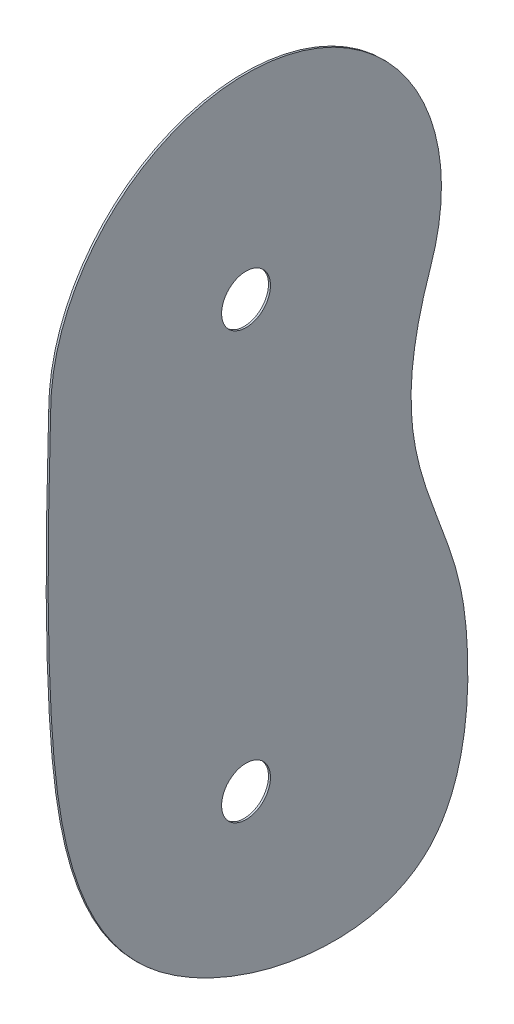
SolidWorks part; units mm, degrees
material "Teras S325"
ref_plane "Front Plane" through (0, 0, 0) normal (0, 0, 1) x (1, 0, 0)
ref_plane "Top Plane" through (0, 0, 0) normal (0, 1, 0) x (1, 0, 0)
ref_plane "Right Plane" through (0, 0, 0) normal (1, 0, 0) x (0, 0, -1)
sketch "Sketch7" plane through (0, 0, 0) normal (1, 0, 0) x (0, 0, -1)
  line L0 (0, 55) -> (0, -55) construction
  line L1 (0, 0) -> (0, 218.0441) construction
  arc A0 (94.4805, 185.2807) -> (-100, 218.0441) centre (0, 218.0441) ccw
  circle A1 centre (0, 218.0441) radius 12.5
  circle A2 centre (0, 0) radius 12.5
  spline S0 degree 3 poles (94.4805, 185.2807) (68.1049, 109.2211) (107.0555, 75.9668) (116.0738, -17.8678) (100.9053, -110.4102) (-83.8199, -71.5417) (-103.5187, 85.3152) (-101.1119, 176.102) (-100, 218.0441) knots 0 0 0 0 0.20409 0.240536 0.364457 0.573406 0.80292 1 1 1 1
  dimension "D1" = 200
  dimension "D2" = 25
  dimension "D3" = 25
extrude "Extrude1" add sketch "Sketch7" along normal mid plane 1
